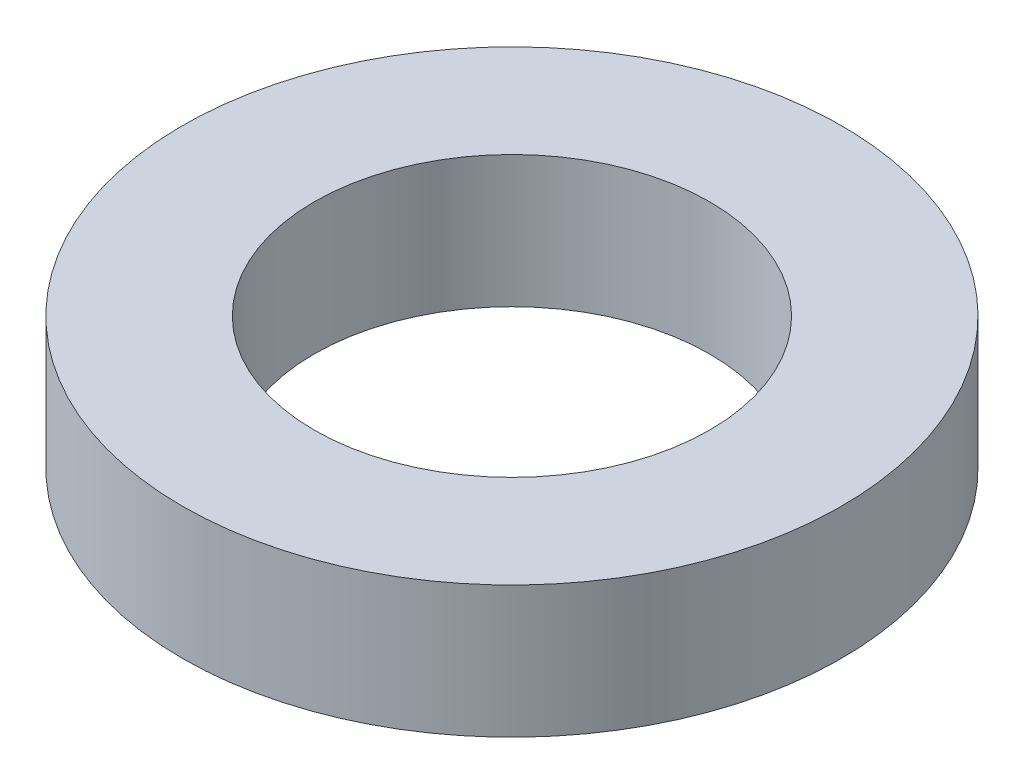
SolidWorks part; units mm, degrees
material "Copper"
ref_plane "Front" through (0, 0, 0) normal (0, 0, 1) x (1, 0, 0)
ref_plane "Top" through (0, 0, 0) normal (0, 1, 0) x (1, 0, 0)
ref_plane "Right" through (0, 0, 0) normal (1, 0, 0) x (0, 0, -1)
sketch "Sketch1" plane through (0, 0, 0) normal (0, 1, 0) x (1, 0, 0)
  circle A0 centre (0, 0) radius 1.5
  circle A1 centre (0, 0) radius 2.5
  dimension "D1" = 3
  dimension "D2" = 5
extrude "Boss-Extrude1" add sketch "Sketch1" along normal blind 1
